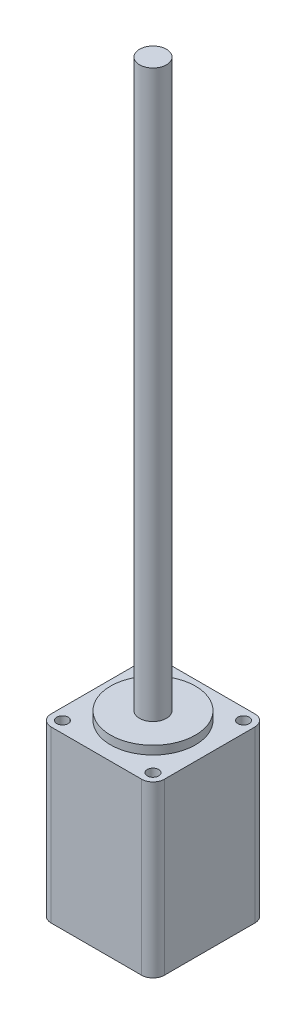
SolidWorks part; units mm, degrees
ref_plane "Front Plane" through (0, 0, 0) normal (0, 0, 1) x (1, 0, 0)
ref_plane "Top Plane" through (0, 0, 0) normal (0, 1, 0) x (1, 0, 0)
ref_plane "Right Plane" through (0, 0, 0) normal (1, 0, 0) x (0, 0, -1)
sketch "Sketch1" plane through (0, 0, 0) normal (0, 1, 0) x (1, 0, 0)
  line L1 (-10, -10) -> (10, -10)
  line L2 (-10, -10) -> (-10, 10)
  line L3 (-10, 10) -> (10, 10)
  line L4 (10, -10) -> (10, 10)
  line L5 (-10, -10) -> (10, 10) construction
  line L6 (-10, 10) -> (10, -10) construction
  point P0 (0, 0)
  dimension "D1" = 20
extrude "Boss-Extrude1" add sketch "Sketch1" along normal blind 30
fillet "Fillet1" radius 2 4 edges at (-10, 15, -10) (-10, 15, 10) (10, 15, -10) (10, 15, 10)
sketch "Sketch2" plane through (0, 30, 0) normal (0, 1, 0) x (1, 0, 0)
  line L1 (-8, -8) -> (8, -8) construction
  line L2 (-8, -8) -> (-8, 8) construction
  line L3 (-8, 8) -> (8, 8) construction
  line L4 (8, -8) -> (8, 8) construction
  line L5 (-8, -8) -> (8, 8) construction
  line L6 (-8, 8) -> (8, -8) construction
  circle A0 centre (-8, 8) radius 1
  circle A1 centre (8, 8) radius 1
  circle A2 centre (8, -8) radius 1
  circle A3 centre (-8, -8) radius 1
  point P0 (0, 0)
  dimension "D2" = 2
  dimension "D1" = 16
extrude "Cut-Extrude1" cut sketch "Sketch2" against normal blind 3
sketch "Sketch3" plane through (0, 30, 0) normal (0, 1, 0) x (1, 0, 0)
  circle A0 centre (0, 0) radius 7.5
  dimension "D1" = 15
extrude "Boss-Extrude2" add sketch "Sketch3" along normal blind 1.5
sketch "Sketch4" plane through (0, 31.5, 0) normal (0, 1, 0) x (1, 0, 0)
  circle A0 centre (0, 0) radius 2.38
  dimension "D1" = 4.76
extrude "Boss-Extrude3" add sketch "Sketch4" along normal blind 100
